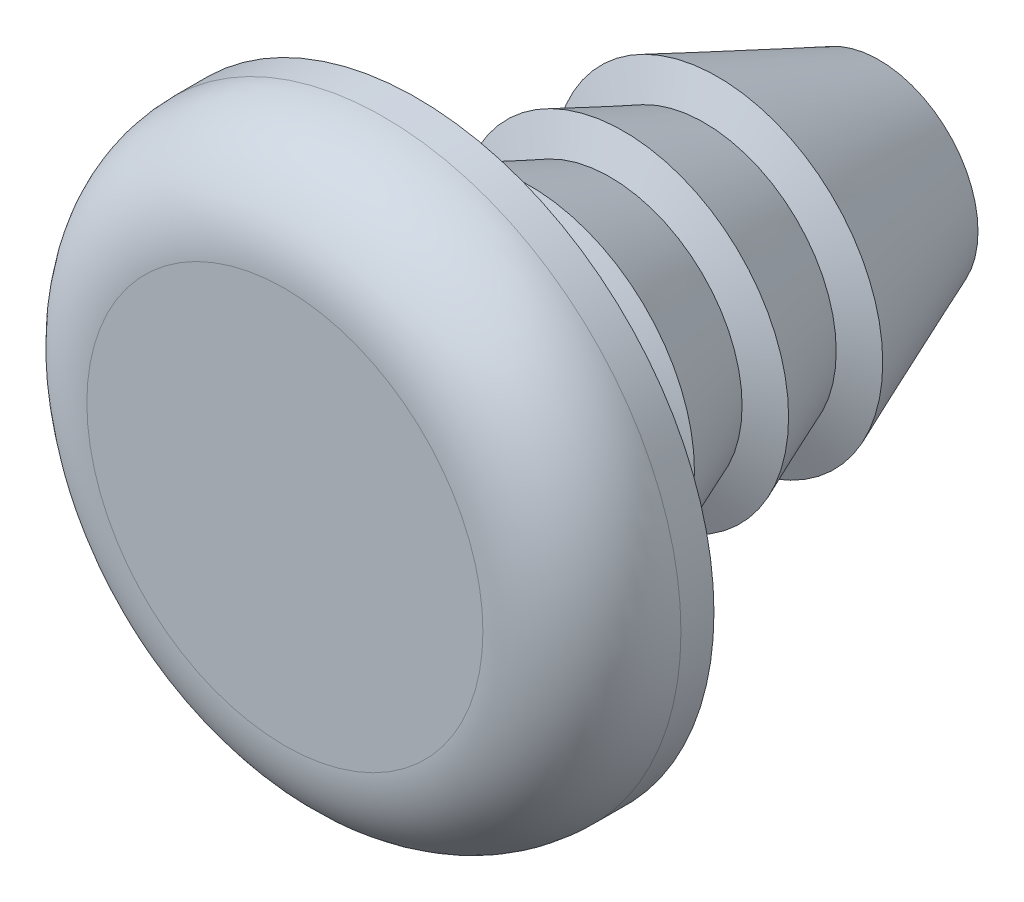
SolidWorks part; units mm, degrees
ref_plane "前视基准面" through (0, 0, 0) normal (0, 0, 1) x (1, 0, 0)
ref_plane "上视基准面" through (0, 0, 0) normal (0, 1, 0) x (1, 0, 0)
ref_plane "右视基准面" through (0, 0, 0) normal (1, 0, 0) x (0, 0, -1)
sketch "草图1" plane through (0, 0, 0) normal (1, 0, 0) x (0, 0, -1)
  line L0 (-35.673, 0) -> (41.1212, 0) construction
  line L1 (0, 4.5) -> (-0.5, 4.5)
  line L2 (-2, 3) -> (-2, 0)
  line L3 (0, 6.4087) -> (0, -8.4454) construction
  line L4 (0, 4.5) -> (0, 2)
  line L5 (0, 2) -> (1.5, 2)
  line L6 (1.5, 2) -> (1.7047, 2.5)
  line L7 (1.7047, 2.5) -> (2.9262, 2)
  line L8 (1.5, 2) -> (8.0695, 2) construction
  line L9 (2.9262, 2) -> (3.1308, 2.5)
  line L10 (3.1308, 2.5) -> (4.3523, 2)
  line L11 (4.3523, 2) -> (4.557, 2.5)
  line L12 (4.557, 2.5) -> (7, 1.5)
  line L13 (7, 1.5) -> (7, 0)
  line L14 (1.7047, 2.5) -> (8.475, 2.5) construction
  line L15 (-2, 0) -> (7, 0)
  arc A0 (-2, 3) -> (-0.5, 4.5) centre (-0.5, 3) cw
  point P21 (-2, 4.5)
  dimension "D8" = 1.5
  dimension "D1" = 4.5
  dimension "D2" = 2
  dimension "D3" = 2.5
  dimension "D4" = 9
  dimension "D5" = 2
  dimension "D6" = 1.5
  dimension "D7" = 1.5
revolve "旋转1" add sketch "草图1" angle 360 about L0
